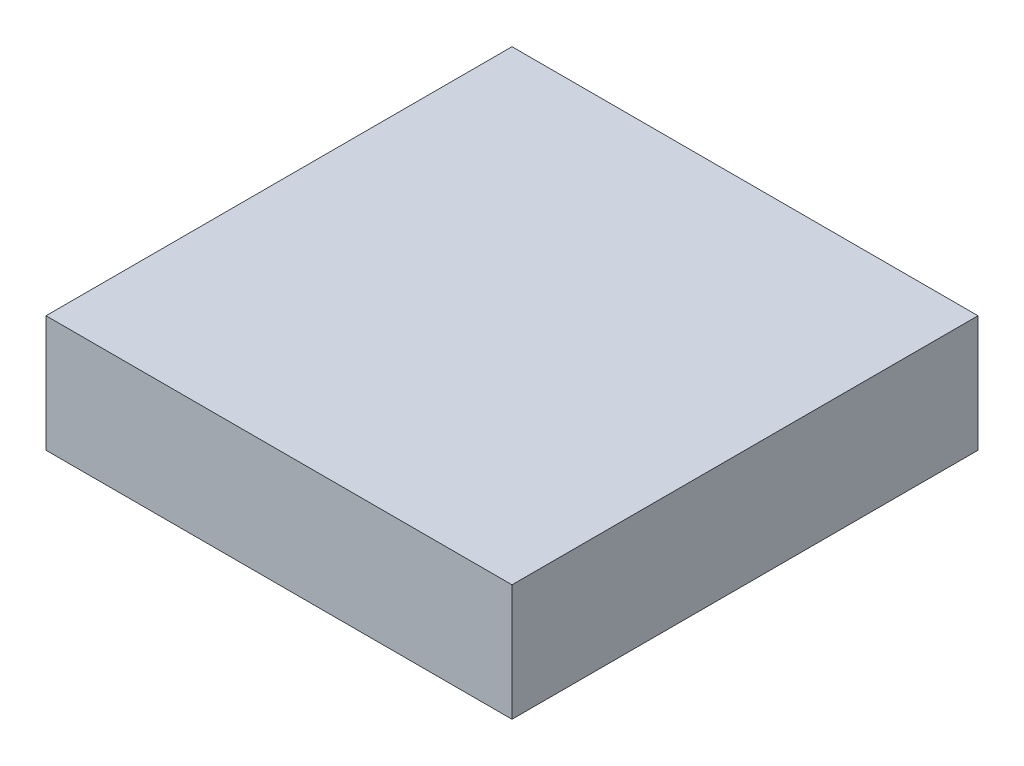
SolidWorks part; units mm, degrees
ref_plane "Front Plane" through (0, 0, 0) normal (0, 0, 1) x (1, 0, 0)
ref_plane "Top Plane" through (0, 0, 0) normal (0, 1, 0) x (1, 0, 0)
ref_plane "Right Plane" through (0, 0, 0) normal (1, 0, 0) x (0, 0, -1)
sketch "Sketch1" plane through (0, 0, 0) normal (0, 1, 0) x (1, 0, 0)
  line L1 (0, 0) -> (4, 0)
  line L2 (0, 0) -> (0, 4)
  line L3 (0, 4) -> (4, 4)
  line L4 (4, 0) -> (4, 4)
  dimension "D1" = 4
  dimension "D2" = 4
extrude "Boss-Extrude1" add sketch "Sketch1" along normal blind 1 contours L3 L4 L1 L2
